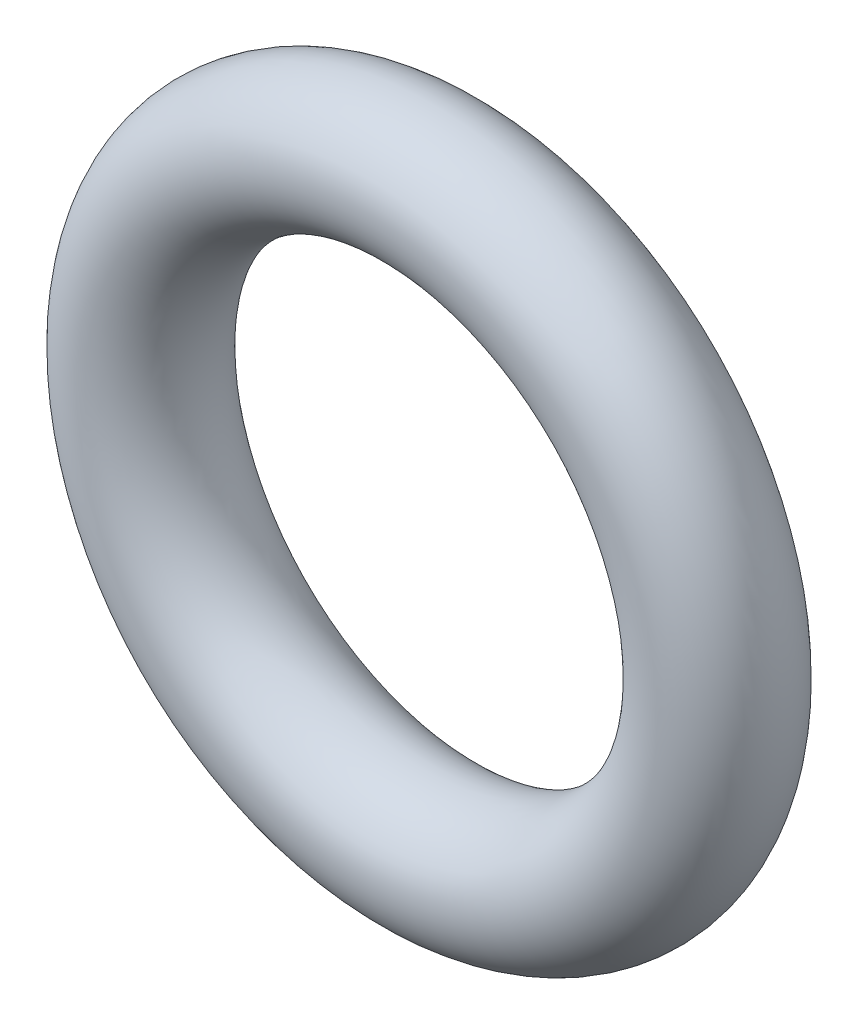
SolidWorks part; units mm, degrees
material "EPDM 60 Durometer"
ref_plane "Front Plane" through (0, 0, 0) normal (0, 0, 1) x (1, 0, 0)
ref_plane "Top Plane" through (0, 0, 0) normal (0, 1, 0) x (1, 0, 0)
ref_plane "Right Plane" through (0, 0, 0) normal (1, 0, 0) x (0, 0, -1)
sketch "Sketch1" plane through (0, 0, 0) normal (0, 0, 1) x (1, 0, 0)
  circle A0 centre (0, 0) radius 3.25
  point P5 (0, 0)
  dimension "D1" = 6.5
sweep "Sweep1" add path "Sketch1" circular profile diameter 1.5 parameters "D3"=1.5
